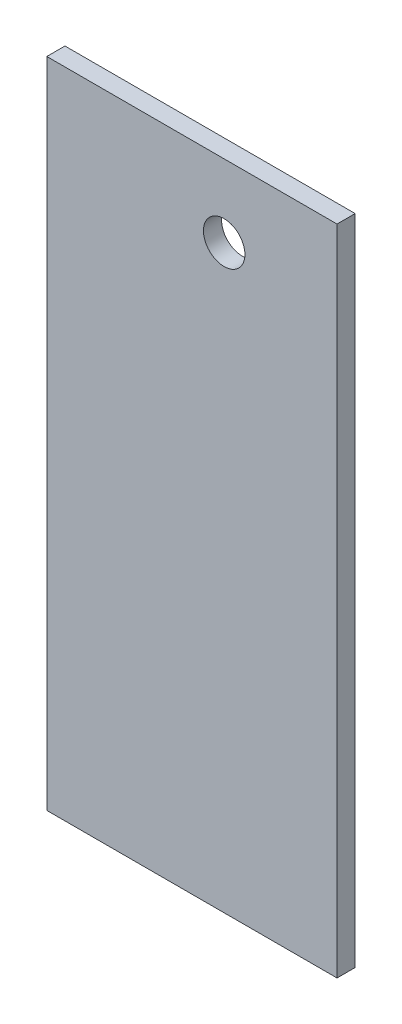
SolidWorks part; units mm, degrees
material "Thornel Mat VMA"
ref_plane "Front Plane" through (0, 0, 0) normal (0, 0, 1) x (1, 0, 0)
ref_plane "Top Plane" through (0, 0, 0) normal (0, 1, 0) x (1, 0, 0)
ref_plane "Right Plane" through (0, 0, 0) normal (1, 0, 0) x (0, 0, -1)
sketch "Sketch1" plane through (0, 0, 0) normal (0, 0, 1) x (1, 0, 0)
  line L0 (0, 77) -> (0, -77) construction
  line L1 (-28.8858, 76) -> (51.1142, 76)
  line L2 (-28.8858, 76) -> (-28.8858, 256)
  line L3 (-28.8858, 256) -> (51.1142, 256)
  line L4 (51.1142, 76) -> (51.1142, 256)
  circle A0 centre (20, 236) radius 5.7159
  dimension "D1" = 160
  dimension "D2" = 20
  dimension "D3" = 180
  dimension "D4" = 80
extrude "Boss-Extrude1" add sketch "Sketch1" along normal blind 5
